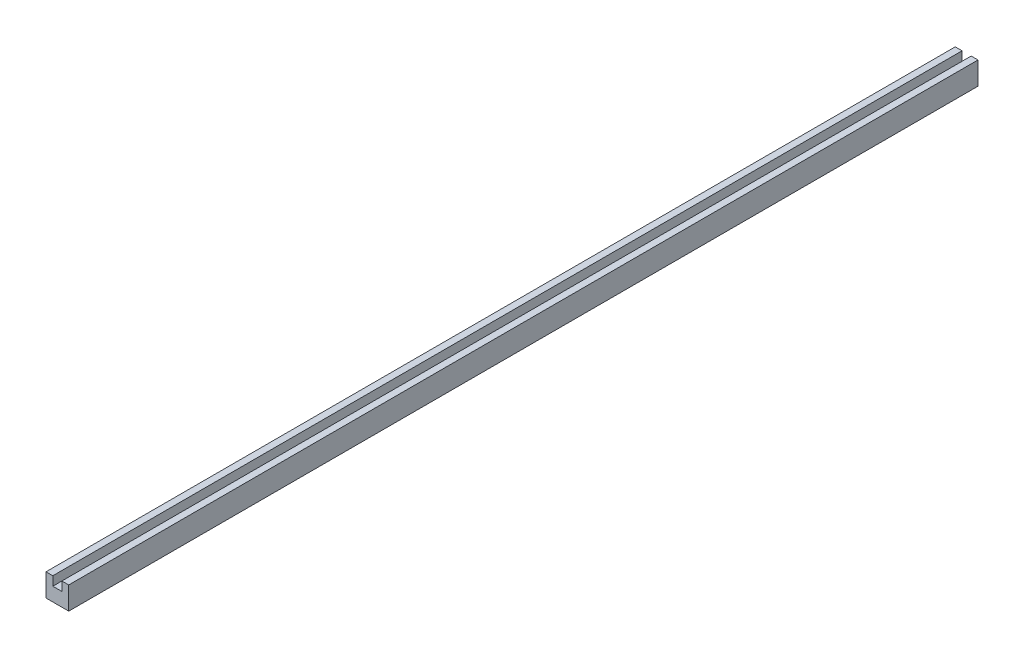
SolidWorks part; units mm, degrees
ref_plane "Front Plane" through (0, 0, 0) normal (0, 0, 1) x (1, 0, 0)
ref_plane "Top Plane" through (0, 0, 0) normal (0, 1, 0) x (1, 0, 0)
ref_plane "Right Plane" through (0, 0, 0) normal (1, 0, 0) x (0, 0, -1)
sketch "Sketch1" plane through (0, 0, 0) normal (0, 0, 1) x (1, 0, 0)
  line L1 (-20.7143, 14.9735) -> (29.2857, 14.9735)
  line L2 (-20.7143, 14.9735) -> (-20.7143, -35.0265)
  line L3 (-20.7143, -35.0265) -> (29.2857, -35.0265)
  line L4 (29.2857, 14.9735) -> (29.2857, -35.0265)
  line L5 (-5.7143, 14.9735) -> (14.2857, 14.9735)
  line L6 (-5.7143, 14.9735) -> (-5.7143, -5.0265)
  line L7 (-5.7143, -5.0265) -> (14.2857, -5.0265)
  line L8 (14.2857, 14.9735) -> (14.2857, -5.0265)
  dimension "D1" = 50
  dimension "D2" = 50
  dimension "D3" = 20
  dimension "D4" = 20
  dimension "D5" = 15
extrude "Boss-Extrude1" add sketch "Sketch1" against normal blind 2000 contours L1 L8 L7 L6 L2 L3 L4
equation "\"BeamLength\"= 2000"
equation "\"BeamWidth\"= 50"
equation "\"BeamHeight\"= 50"
equation "\"ChannelWidth\"= 20"
equation "\"ChannelDepth\"= 20"
equation "\"D1@Sketch1\"=\"BeamWidth\""
equation "\"D2@Sketch1\"=\"BeamHeight\""
equation "\"D3@Sketch1\"=\"ChannelDepth\""
equation "\"D4@Sketch1\"=\"ChannelWidth\""
equation "\"D5@Sketch1\"=(\"BeamWidth\"-\"ChannelWidth\")/2"
equation "\"D1@Boss-Extrude1\"=\"BeamLength\""
